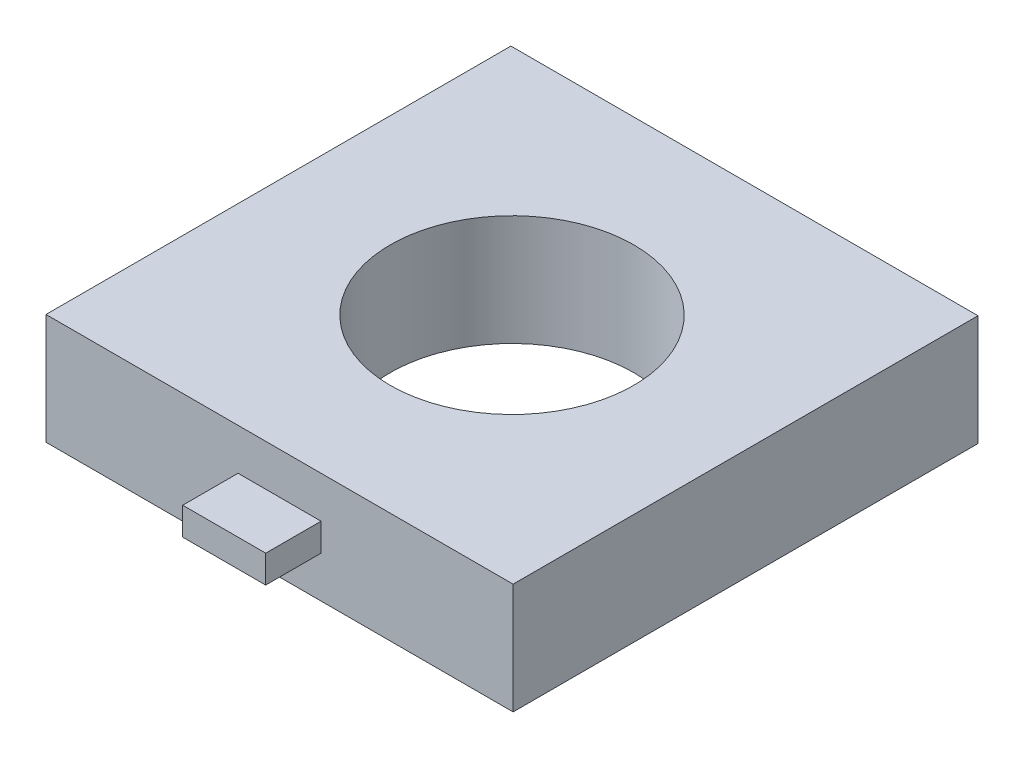
SolidWorks part; units mm, degrees
ref_plane "Alzado" through (0, 0, 0) normal (0, 0, 1) x (1, 0, 0)
ref_plane "Planta" through (0, 0, 0) normal (0, 1, 0) x (1, 0, 0)
ref_plane "Vista lateral" through (0, 0, 0) normal (1, 0, 0) x (0, 0, -1)
sketch "Croquis1" plane through (0, 0, 0) normal (0, 0, 1) x (1, 0, 0)
  line L0 (0, 0) -> (42.2, 0)
  line L1 (42.2, 0) -> (42.2, -10)
  line L2 (42.2, -10) -> (0, -10)
  line L3 (0, -10) -> (0, 0)
  dimension "D1" = 10
  dimension "D2" = 42.2
extrude "Saliente-Extruir1" add sketch "Croquis1" along normal blind 42
sketch "Croquis2" plane through (0, 0, 42) normal (0, 0, 1) x (1, 0, 0)
  line L0 (21.1, 0) -> (21.1, -10) construction
  line L1 (0, -5) -> (42.2, -5) construction
  line L3 (17.35, -6.25) -> (24.85, -6.25)
  line L4 (0, 0) -> (0, -10)
  line L5 (0, -10) -> (42.2, -10)
  line L6 (42.2, -10) -> (42.2, 0)
  line L7 (42.2, 0) -> (0, 0)
  line L8 (0, 0) -> (0, -10) construction
  line L9 (0, -10) -> (42.2, -10) construction
  line L10 (42.2, -10) -> (42.2, 0) construction
  line L11 (42.2, 0) -> (0, 0) construction
  line L12 (17.35, -6.25) -> (17.35, -3.75)
  line L13 (17.35, -3.75) -> (24.85, -3.75)
  line L14 (24.85, -6.25) -> (24.85, -3.75)
  dimension "D2" = 1.25
  dimension "D3" = 1.25
  dimension "D4" = 3.75
  dimension "D5" = 3.75
  dimension "D1" = 0
extrude "Saliente-Extruir2" add sketch "Croquis2" along normal blind 5
sketch "Croquis3" plane through (0, 0, 0) normal (0, 1, 0) x (1, 0, 0)
  line L0 (21.1, -42) -> (21.1, 0) construction
  line L1 (24.85, -42) -> (17.35, -42) construction
  line L2 (42.2, 0) -> (0, 0) construction
  line L3 (0, -21) -> (42.2, -21) construction
  line L4 (0, -42) -> (0, 0) construction
  line L5 (42.2, -42) -> (42.2, 0) construction
  circle A0 centre (21.1, -21) radius 11
  dimension "D1" = 22
extrude "Cortar-Extruir1" cut sketch "Croquis3" against normal blind 25
